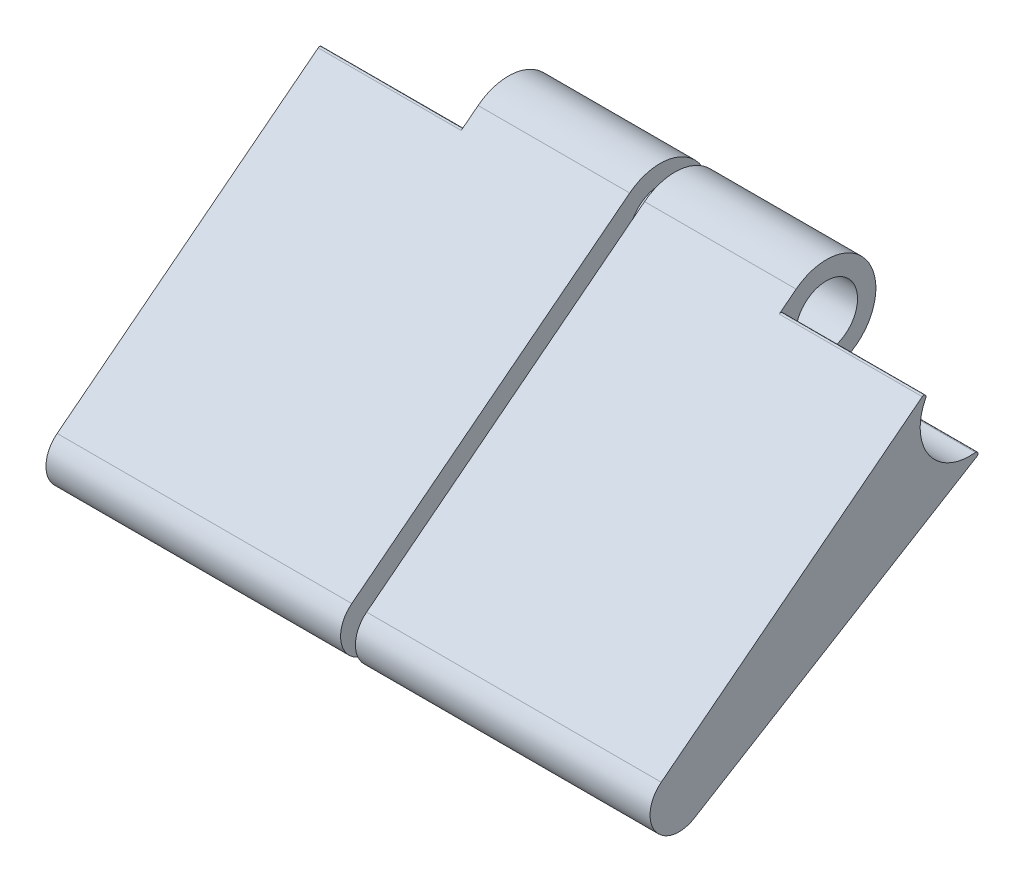
SolidWorks part; units mm, degrees
ref_plane "前视基准面" through (0, 0, 0) normal (0, 0, 1) x (1, 0, 0)
ref_plane "上视基准面" through (0, 0, 0) normal (0, 1, 0) x (1, 0, 0)
ref_plane "右视基准面" through (0, 0, 0) normal (1, 0, 0) x (0, 0, -1)
sketch "草图1" plane through (70.25, 0, 0) normal (1, 0, 0) x (0, 0, -1)
  line L0 (-94.8502, -49.0729) -> (-81.8954, -41.1904)
  line L1 (-96.2683, -47.019) -> (-84.306, -37.6987)
  circle A0 centre (-83, -39.375) radius 1.3351
  circle A2 centre (-95.5, -48.005) radius 1.25
  circle A3 centre (-83, -39.375) radius 2.125
  arc M8 (-83, -37.25) -> (-83.3208, -41.4756) centre (-83, -39.375) ccw
  line M9 (-83.3208, -41.4756) -> (-73.8675, -42.9194)
  circle M13 centre (-83, -39.375) radius 1.3351
  dimension "D1" = 2.5
  dimension "D2" = 12.5
  dimension "D3" = 8.63
extrude "凸台-拉伸1" add sketch "草图1" against normal up to surface (12.6805 mm away) contours A3 M8 M13 | A2 L0 L1 M9 M8 | A2 | A3 L0 M9
sketch "草图2" plane through (70.25, 0, 0) normal (1, 0, 0) x (0, 0, -1)
  circle A0 centre (-83, -39.375) radius 1.3351
  circle A1 centre (-83, -39.375) radius 2.125
extrude "切除-拉伸1" cut sketch "草图2" against normal up to vertex (6.1562 mm away)
sketch "草图3" plane through (70.25, 0, 0) normal (1, 0, 0) x (0, 0, -1)
  line L1 (-85.7378, -37.4467) -> (-84.0675, -37.4467)
  line L2 (-84.306, -37.6987) -> (-96.2683, -47.019)
  line L3 (-94.8502, -49.0729) -> (-81.8954, -41.1904)
  line L4 (-85.0333, -38.2654) -> (-96.2683, -47.019)
  line L5 (-94.8502, -49.0729) -> (-82.683, -41.6696)
  line L6 (-85.7378, -37.4467) -> (-85.7378, -38.5732)
  line L7 (-85.7378, -38.5732) -> (-84.0675, -38.5732)
  line L8 (-84.0675, -37.4467) -> (-84.0675, -38.5732)
  line L9 (-83.0728, -40.8267) -> (-81.5128, -40.8267)
  line L10 (-83.0728, -40.8267) -> (-83.0728, -42.1268)
  line L11 (-83.0728, -42.1268) -> (-81.5128, -42.1268)
  line L12 (-81.5128, -40.8267) -> (-81.5128, -42.1268)
  arc A0 (-82.7469, -41.4849) -> (-82.683, -41.6696) centre (-82.735, -41.5842) cw
  arc A1 (-84.8832, -38.3906) -> (-85.0333, -38.2654) centre (-84.9719, -38.3443) ccw
  arc A2 (-84.306, -37.6987) -> (-81.8954, -41.1904) centre (-83, -39.375) ccw
  arc A3 (-96.2683, -47.019) -> (-94.8502, -49.0729) centre (-95.5, -48.005) ccw
  arc A4 (-84.8832, -38.3906) -> (-82.7469, -41.4849) centre (-83, -39.375) ccw
  arc A5 (-96.2683, -47.019) -> (-94.8502, -49.0729) centre (-95.5, -48.005) ccw
  circle A6 centre (-83, -39.375) radius 1.3351 construction
  arc M11 (-81.8954, -41.1904) -> (-84.306, -37.6987) centre (-83, -39.375) cw
  line M12 (-84.306, -37.6987) -> (-96.2683, -47.019)
  line M14 (-94.8502, -49.0729) -> (-81.8954, -41.1904)
  dimension "D2" = 0.1
  dimension "D1" = 0
extrude "切除-拉伸5" cut sketch "草图3" against normal up to vertex (6.1562 mm away) and the other way through all contours L8 L1 L6 L7 M12 M11 | A1 M11 M12 | L12 L9 L10 L5 L11 M11 M14 | A0 M11 M14
ref_plane "基准面4" through (57.25, 0, 0) normal (1, 0, 0) x (0, 0, -1)
mirror "镜向3" about plane through (57.25, 0, 0) normal (1, 0, 0) of bodies 104
